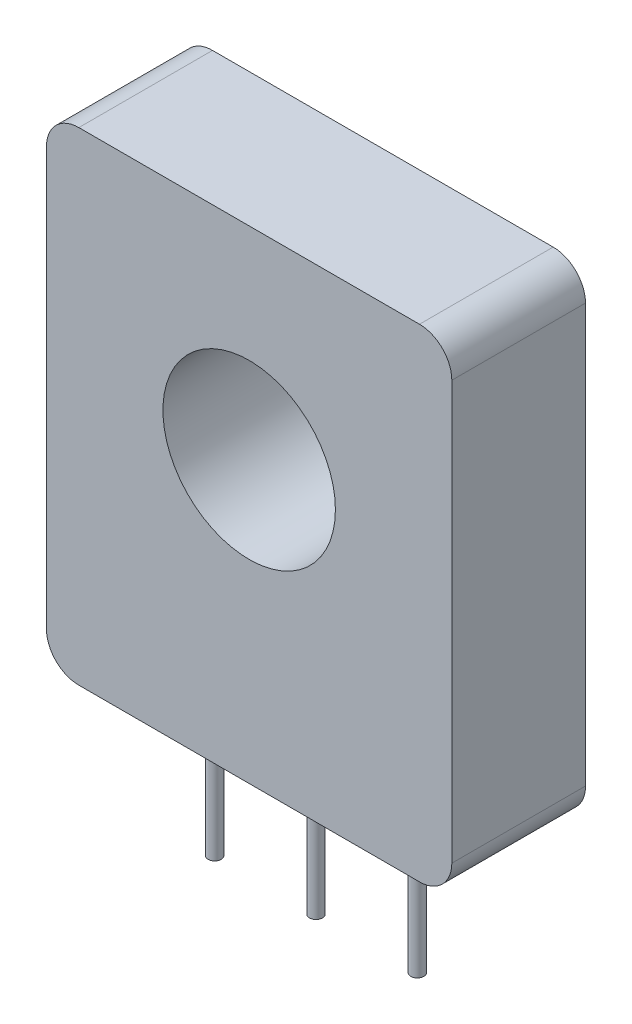
SolidWorks part; units mm, degrees
ref_plane "Front" through (0, 0, 0) normal (0, 0, 1) x (1, 0, 0)
ref_plane "Top" through (0, 0, 0) normal (0, 1, 0) x (1, 0, 0)
ref_plane "Right" through (0, 0, 0) normal (1, 0, 0) x (0, 0, -1)
sketch "Sketch1" plane through (0, 0, 0) normal (0, 0, 1) x (1, 0, 0)
  line L1 (0.75, 0) -> (8.65, 0)
  line L2 (0, 0.75) -> (0, 10.45)
  line L3 (0.75, 11.2) -> (8.65, 11.2)
  line L4 (9.4, 0.75) -> (9.4, 10.45)
  arc A0 (0, 10.45) -> (0.75, 11.2) centre (0.75, 10.45) cw
  arc A1 (8.65, 11.2) -> (9.4, 10.45) centre (8.65, 10.45) cw
  arc A2 (9.4, 0.75) -> (8.65, 0) centre (8.65, 0.75) cw
  arc A3 (0.75, 0) -> (0, 0.75) centre (0.75, 0.75) cw
  point P13 (0, 0)
  dimension "D3" = 0.75
  dimension "D1" = 11.2
  dimension "D2" = 9.4
extrude "ext-body" add sketch "Sketch1" along normal mid plane 3.1
sketch "Sketch2" plane through (0, 0, 1.55) normal (0, 0, 1) x (1, 0, 0)
  circle A0 centre (4.7, 6.5) radius 2
  dimension "D3" = 4
  dimension "D1" = 6.5
  dimension "D2" = 4.7
extrude "cut-pot_hole" cut sketch "Sketch2" against normal through all both and the other way through all
sketch "Sketch3" plane through (0, 0, 1.55) normal (0, 0, 1) x (1, 0, 0)
  line L0 (3.0948, 5.9403) -> (3.8301, 7.9606)
  line L1 (4.7, 0) -> (4.7, 11.2) construction
  line L2 (8.65, 11.2) -> (0.75, 11.2) construction
  line L3 (0.75, 0) -> (8.65, 0) construction
  arc A0 (3.0948, 5.9403) -> (3.8301, 7.9606) centre (4.7, 6.5) ccw
  dimension "D1" = 3.4
  dimension "D2" = 2.15
  dimension "D3" = 20
extrude "ext-pot" [suppressed] add sketch "Sketch3" along normal blind 1.5 and the other way up to surface separate body
sketch "Sketch4" [suppressed] plane through (0, 0, 3.2) normal (0, 0, 1) x (1, 0, 0)
  line L3 (4.9779, 6.1602) -> (4.4565, 4.7276)
  line L4 (4.9779, 6.1602) -> (4.4565, 4.7276)
  arc A3 (4.4565, 4.7276) -> (4.9779, 6.1602) centre (5.25, 5.25) ccw
  arc A4 (4.4565, 4.7276) -> (4.9779, 6.1602) centre (5.25, 5.25) ccw
  dimension "D1" = 0.75
extrude "cut-pot_inner" [suppressed] cut sketch "Sketch4" against normal blind 1.5
sketch "Sketch5" plane through (0, 0, 0) normal (0, -1, 0) x (1, 0, 0)
  line L0 (9.4, 0) -> (0, 0) construction
  line L1 (9.4, 1.55) -> (9.4, -1.55) construction
  line L2 (2.35, -1.55) -> (2.35, 1.55) construction
  line L3 (0.75, -1.55) -> (8.65, -1.55) construction
  line L4 (0.75, 1.55) -> (8.65, 1.55) construction
  line L5 (7.05, 1.55) -> (7.05, -1.55) construction
  line L6 (4.7, 1.55) -> (4.7, -1.55) construction
  circle A0 centre (2.35, 0) radius 0.15
  circle A1 centre (4.7, 0) radius 0.15
  circle A2 centre (7.05, 0) radius 0.15
  point P15 (7.05, 0)
  point P16 (4.7, 0)
  point P17 (2.35, 0)
  dimension "D4" = 0.3
  dimension "D5" = 0.3
  dimension "D6" = 0.3
  dimension "D1" = 4.7
  dimension "D2" = 2.35
  dimension "D3" = 2.35
extrude "ext-pins" add sketch "Sketch5" along normal blind 3.4
equation "\"len-body\"= 9.4mm"
equation "\"rad-body\"= 0.75mm"
equation "\"th-body\"= 3.1mm"
equation "\"rad-hole\"= 4mm"
equation "\"rad-pot\"= 3.4mm"
equation "\"len-potbar\"= 2.15mm"
equation "\"th-pot\"= 1.5mm"
equation "\"D2@Sketch1\"=\"len-body\""
equation "\"D3@Sketch1\"=\"rad-body\""
equation "\"D1@ext-body\" = \"th-body\""
equation "\"D2@Sketch2\"=\"len-body\"/2"
equation "\"D3@Sketch2\"=\"rad-hole\""
equation "\"D1@Sketch3\"=\"rad-pot\""
equation "\"D2@Sketch3\"=\"len-potbar\""
equation "\"ang-pot-zero\"= 20deg"
equation "\"ang-pot-max\"= 45deg"
equation "\"D1@ext-pot\" = \"th-pot\""
equation "\"D1@cut-pot_inner\" = \"th-pot\""
equation "\"D3@Sketch3\"=\"ang-pot-zero\""
equation "\"D1@Sketch5\"=\"len-body\"/2"
equation "\"len-midpin\"= \"len-body\" / 2"
equation "\"len-outerpins\"= \"len-midpin\" / 2"
equation "\"D3@Sketch5\"=\"len-outerpins\""
equation "\"D2@Sketch5\"=\"len-outerpins\""
equation "\"rad-pins\"= 0.3mm"
equation "\"D4@Sketch5\"=\"rad-pins\""
equation "\"D5@Sketch5\"=\"rad-pins\""
equation "\"D6@Sketch5\"=\"rad-pins\""
equation "\"len-pin\"= 3.4mm"
equation "\"D1@ext-pins\" = \"len-pin\""
